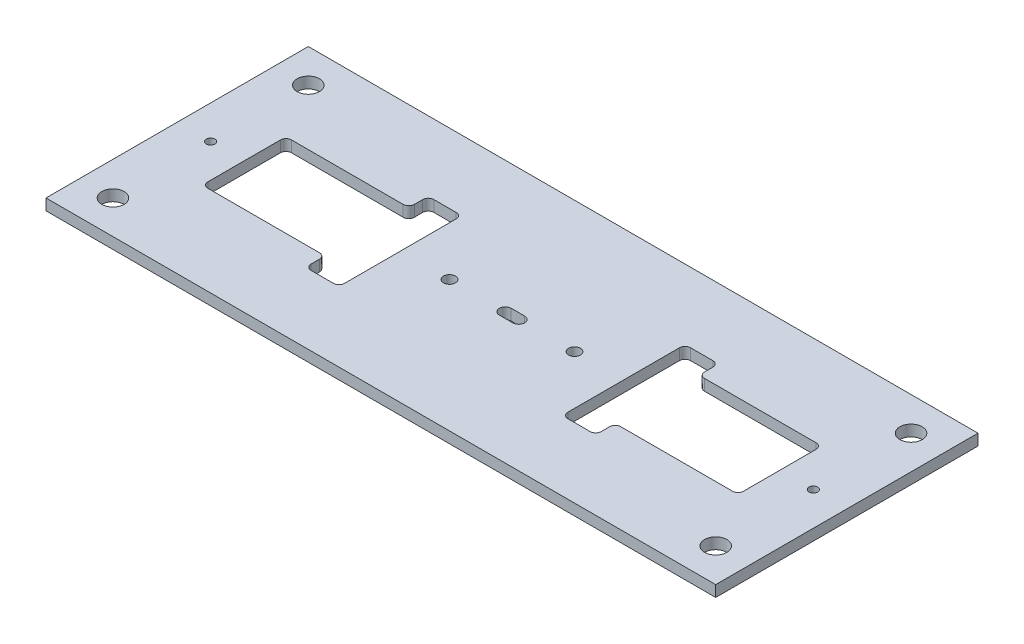
SolidWorks part; units mm, degrees
material "6061 Alloy"
ref_plane "Front Plane" through (0, 0, 0) normal (0, 0, 1) x (1, 0, 0)
ref_plane "Top Plane" through (0, 0, 0) normal (0, 1, 0) x (1, 0, 0)
ref_plane "Right Plane" through (0, 0, 0) normal (1, 0, 0) x (0, 0, -1)
sketch "Sketch1" plane through (0, 0, 0) normal (0, 1, 0) x (1, 0, 0)
  line L0 (381, 0) -> (381, 149.225)
  line L1 (0, 0) -> (381, 0)
  line L3 (0, 149.225) -> (381, 149.225)
  line L5 (190.5, 0) -> (190.5, 149.225) construction
  line L6 (342.9, 95.25) -> (342.9, 53.975)
  line L7 (41.275, 98.425) -> (123.825, 98.425)
  line L8 (127, 95.25) -> (127, 53.975)
  line L9 (123.825, 50.8) -> (41.275, 50.8)
  line L13 (0, 0) -> (0, 149.225)
  line L15 (38.1, 95.25) -> (38.1, 53.975)
  line L16 (38.1, 98.425) -> (38.1, 149.225) construction
  line L17 (38.1, 50.8) -> (38.1, 0) construction
  line L18 (257.175, 50.8) -> (339.725, 50.8)
  line L19 (254, 95.25) -> (254, 53.975)
  line L20 (339.725, 98.425) -> (257.175, 98.425)
  line L21 (0, 74.6125) -> (381, 74.6125) construction
  arc A0 (127, 53.975) -> (123.825, 50.8) centre (123.825, 53.975) cw
  arc A1 (123.825, 98.425) -> (127, 95.25) centre (123.825, 95.25) cw
  arc A4 (38.1, 53.975) -> (41.275, 50.8) centre (41.275, 53.975) ccw
  arc A5 (38.1, 95.25) -> (41.275, 98.425) centre (41.275, 95.25) cw
  arc A6 (342.9, 95.25) -> (339.725, 98.425) centre (339.725, 95.25) ccw
  arc A7 (342.9, 53.975) -> (339.725, 50.8) centre (339.725, 53.975) cw
  arc A8 (257.175, 98.425) -> (254, 95.25) centre (257.175, 95.25) ccw
  arc A9 (254, 53.975) -> (257.175, 50.8) centre (257.175, 53.975) ccw
  point P22 (127, 50.8)
  point P25 (127, 98.425)
  point P37 (254, 98.425)
  point P38 (254, 50.8)
  dimension "D4" = 3.175
  dimension "D7" = 88.9
  dimension "D3" = 3.175
  dimension "D1" = 381
  dimension "D2" = 149.225
  dimension "D5" = 190.5
  dimension "D6" = 47.625
  dimension "D8" = 38.1
extrude "Boss-Extrude1" add sketch "Sketch1" along normal blind 6.35
hole_wizard "1/4 Clearance Hole1" positions "Sketch2" profile "Sketch3" hole size "1/4" standard "ANSI Inch" end condition through all
sketch "Sketch2" plane through (0, 6.35, 0) normal (0, 1, 0) x (1, 0, 0)
  line L0 (190.5, 0) -> (190.5, 149.225) construction
  line L1 (0, 0) -> (381, 0) construction
  line L2 (381, 149.225) -> (0, 149.225) construction
  line L3 (127, 74.6125) -> (254, 74.6125) construction
  line L6 (127, 95.25) -> (127, 53.975) construction
  line L8 (254, 95.25) -> (254, 53.975) construction
  point P0 (154.94, 74.6125)
  point P2 (186.69, 74.6125)
  point P12 (194.31, 74.6125)
  point P13 (226.06, 74.6125)
  dimension "D1" = 3.81
  dimension "D2" = 31.75
sketch "Sketch3" plane through (154.94, 6.35, -74.6125) normal (1, 0, 0) x (0, 0, 1)
  line L0 (0, 0) -> (0, 6.35)
  line L1 (0, 6.35) -> (3.3782, 6.35)
  line L2 (3.3782, 6.35) -> (3.3782, 0)
  line L5 (3.3782, 0) -> (0, 0)
  line L11 (0, -6.35) -> (0, 107.95) construction
  dimension "Thru Hole Dia." = 6.7564
  dimension "Thru Hole Depth" = 6.35
sketch "Sketch4" plane through (0, 6.35, 0) normal (0, 1, 0) x (1, 0, 0)
  line L0 (186.69, 74.6125) -> (194.31, 74.6125) construction
  line L1 (186.69, 77.9907) -> (194.31, 77.9907)
  line L2 (186.69, 71.2343) -> (194.31, 71.2343)
  arc A0 (186.69, 77.9907) -> (186.69, 71.2343) centre (186.69, 74.6125) ccw
  arc A1 (194.31, 71.2343) -> (194.31, 77.9907) centre (194.31, 74.6125) ccw
  circle A2 centre (186.69, 74.6125) radius 3.3782 construction
  point P4 (190.5, 74.6125)
extrude "Cut-Extrude1" cut sketch "Sketch4" against normal through all
sketch "Sketch5" plane through (0, 6.35, 0) normal (0, 1, 0) x (1, 0, 0)
  line L0 (381, 149.225) -> (0, 149.225) construction
  line L1 (0, 0) -> (381, 0) construction
  line L2 (0, 149.225) -> (0, 0) construction
  line L3 (190.5, 149.225) -> (190.5, 0) construction
  line L4 (0, 74.6125) -> (381, 74.6125) construction
  line L5 (381, 0) -> (381, 149.225) construction
  point P0 (19.05, 130.175)
  point P2 (19.05, 19.05)
  point P4 (19.05, 74.6125)
  point P5 (361.95, 19.05)
  point P10 (361.95, 74.6125)
  point P13 (361.95, 130.175)
  point P18 (19.05, 74.6125)
  dimension "D1" = 19.05
  dimension "D2" = 19.05
  dimension "D3" = 19.05
hole_wizard "1/2 (0.5) Diameter Hole1" positions "3DSketch1" profile "Sketch6" hole size "1/2" standard "ANSI Inch" end condition through all
sketch3d "3DSketch1"
  point P0 (19.05, 6.35, -130.175)
  point P6 (19.05, 6.35, -19.05)
  point P9 (361.95, 6.35, -130.175)
  point P15 (361.95, 6.35, -19.05)
sketch "Sketch6" plane through (19.05, 6.35, -130.175) normal (1, 0, 0) x (0, 0, 1)
  line L0 (0, 0) -> (0, 6.35)
  line L1 (0, 6.35) -> (6.35, 6.35)
  line L2 (6.35, 6.35) -> (6.35, 0)
  line L5 (6.35, 0) -> (0, 0)
  line L11 (0, -6.35) -> (0, 107.95) construction
  dimension "Thru Hole Dia." = 12.7
  dimension "Thru Hole Depth" = 6.35
hole_wizard "#10 (0.1935) Diameter Hole1" positions "Sketch7" profile "Sketch8" hole size "#10" standard "ANSI Inch" end condition through all
sketch "Sketch7" plane through (0, 6.35, 0) normal (0, 1, 0) x (1, 0, 0)
  point P0 (19.05, 74.6125)
  point P3 (361.95, 74.6125)
sketch "Sketch8" plane through (19.05, 6.35, -74.6125) normal (1, 0, 0) x (0, 0, 1)
  line L0 (0, 0) -> (0, 6.35)
  line L1 (0, 6.35) -> (2.4574, 6.35)
  line L2 (2.4574, 6.35) -> (2.4574, 0)
  line L5 (2.4574, 0) -> (0, 0)
  line L11 (0, -6.35) -> (0, 107.95) construction
  dimension "Thru Hole Dia." = 4.9149
  dimension "Thru Hole Depth" = 6.35
sketch "Sketch9" plane through (0, 6.35, 0) normal (0, 1, 0) x (1, 0, 0)
  line L1 (107.95, 95.25) -> (127, 95.25)
  line L2 (107.95, 95.25) -> (107.95, 109.5375)
  line L3 (107.95, 109.5375) -> (127, 109.5375)
  line L4 (127, 95.25) -> (127, 109.5375)
  line L5 (127, 53.975) -> (127, 95.25) construction
  line L6 (127, 74.6125) -> (254, 74.6125) construction
  line L7 (254, 95.25) -> (254, 53.975) construction
  line L8 (190.5, 0) -> (190.5, 149.225) construction
  line L9 (0, 0) -> (381, 0) construction
  line L10 (381, 149.225) -> (0, 149.225) construction
  line L11 (107.95, 39.6875) -> (127, 39.6875)
  line L12 (127, 53.975) -> (127, 39.6875)
  line L13 (107.95, 53.975) -> (127, 53.975)
  line L14 (107.95, 53.975) -> (107.95, 39.6875)
  line L15 (273.05, 53.975) -> (273.05, 39.6875)
  line L16 (273.05, 53.975) -> (254, 53.975)
  line L17 (254, 53.975) -> (254, 39.6875)
  line L18 (273.05, 39.6875) -> (254, 39.6875)
  line L19 (273.05, 109.5375) -> (254, 109.5375)
  line L20 (254, 95.25) -> (254, 109.5375)
  line L21 (273.05, 95.25) -> (254, 95.25)
  line L22 (273.05, 95.25) -> (273.05, 109.5375)
  line L23 (123.825, 98.425) -> (41.275, 98.425) construction
  point P4 (107.95, 82.3744)
  point P31 (127, 84.1375)
  point P32 (107.95, 76.6034)
  dimension "D1" = 11.1125
  dimension "D2" = 19.05
extrude "Cut-Extrude2" cut sketch "Sketch9" against normal through all
fillet "Fillet1" radius 3.175 12 edges at (273.05, 3.175, -50.8) (273.05, 3.175, -39.6875) (254, 3.175, -39.6875) (254, 3.175, -109.5375) (273.05, 3.175, -109.5375) (273.05, 3.175, -98.425) (127, 3.175, -39.6875) (127, 3.175, -109.5375) (107.95, 3.175, -109.5375) (107.95, 3.175, -50.8) (107.95, 3.175, -39.6875) (107.95, 3.175, -98.425)
